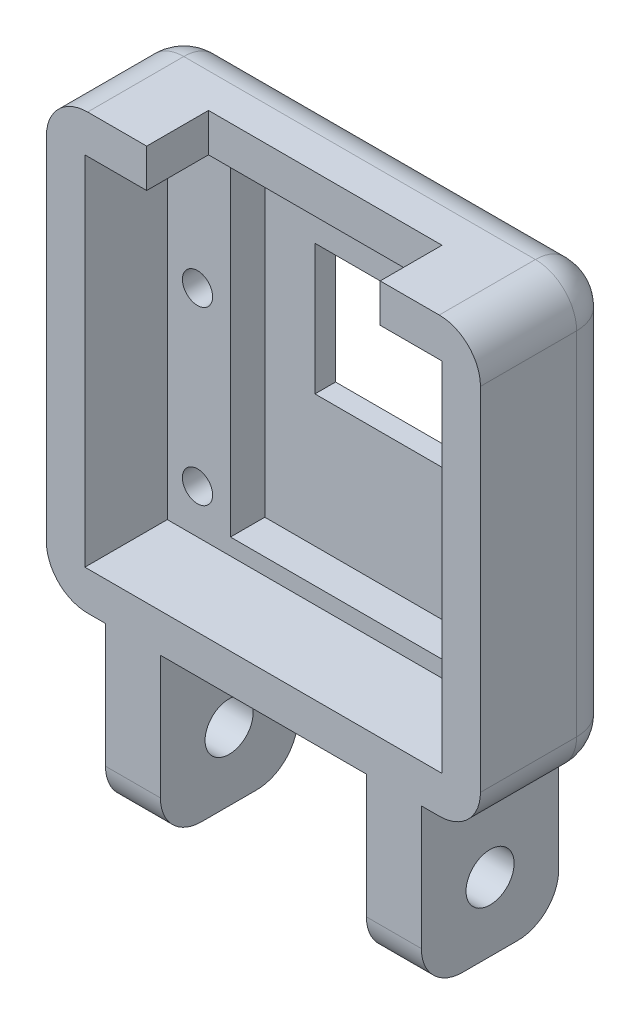
SolidWorks part; units mm, degrees
ref_plane "Front Plane" through (0, 0, 0) normal (0, 0, 1) x (1, 0, 0)
ref_plane "Top Plane" through (0, 0, 0) normal (0, 1, 0) x (1, 0, 0)
ref_plane "Right Plane" through (0, 0, 0) normal (1, 0, 0) x (0, 0, -1)
sketch "Sketch8" plane through (0, 0, 0) normal (0, 0, 1) x (1, 0, 0)
  line L1 (15.8, -15.8) -> (-15.8, -15.8)
  line L2 (15.8, -15.8) -> (15.8, 15.8)
  line L3 (15.8, 15.8) -> (-15.8, 15.8)
  line L4 (-15.8, -15.8) -> (-15.8, 15.8)
  line L5 (15.8, -15.8) -> (-15.8, 15.8) construction
  line L6 (15.8, 15.8) -> (-15.8, -15.8) construction
  line L7 (13, -13) -> (-13, -13)
  line L8 (13, -13) -> (13, 13)
  line L9 (13, 13) -> (-13, 13)
  line L10 (-13, -13) -> (-13, 13)
  line L11 (13, -13) -> (-13, 13) construction
  line L12 (13, 13) -> (-13, -13) construction
  line L13 (-10.8, 2.7) -> (10.8, 2.7)
  line L14 (-10.8, 2.7) -> (-10.8, -9.8)
  line L15 (-10.8, -9.8) -> (10.8, -9.8)
  line L16 (10.8, 2.7) -> (10.8, -9.8)
  line L17 (-4.75, -2.2) -> (4.75, -2.2)
  line L18 (-4.75, -2.2) -> (-4.75, 7.3)
  line L19 (-4.75, 7.3) -> (4.75, 7.3)
  line L20 (4.75, -2.2) -> (4.75, 7.3)
  line L21 (8.4, -11.8) -> (-8.4, -11.8)
  line L22 (8.4, -11.8) -> (8.4, 11.8)
  line L23 (8.4, 11.8) -> (-8.4, 11.8)
  line L24 (-8.4, -11.8) -> (-8.4, 11.8)
  line L25 (8.4, -11.8) -> (-8.4, 11.8) construction
  line L26 (-9, 15.8) -> (9, 15.8)
  line L27 (-9, 15.8) -> (-9, 13)
  line L28 (-9, 13) -> (9, 13)
  line L29 (9, 15.8) -> (9, 13)
  line L30 (8.4, 11.8) -> (-8.4, -11.8) construction
  point P0 (0, 0)
  point P5 (0, 0)
  point P13 (0, 7.3)
  point P27 (0, 0)
  dimension "D2" = 9.5
  dimension "D1" = 2.8
  dimension "D3" = 7.3
  dimension "D4" = 1.2
  dimension "D5" = 16.8
sketch "Sketch2" plane through (0, 0, 0) normal (0, 0, 1) x (1, 0, 0)
  line L1 (15.8, 15.8) -> (-15.8, 15.8)
  line L2 (15.8, 15.8) -> (15.8, -15.8)
  line L3 (15.8, -15.8) -> (-15.8, -15.8)
  line L4 (-15.8, 15.8) -> (-15.8, -15.8)
  line L5 (15.8, 15.8) -> (-15.8, -15.8) construction
  line L6 (15.8, -15.8) -> (-15.8, 15.8) construction
  point P0 (0, 0)
  dimension "D1" = 31.6
extrude "Boss-Extrude1" add sketch "Sketch2" along normal blind 10 separate body
sketch "Sketch13" plane through (0, -15.8, 0) normal (0, -1, 0) x (1, 0, 0)
  line L0 (-15.8, 10) -> (15.8, 10) construction
  line L1 (-11.5, 10) -> (-7.5, 10)
  line L2 (-11.5, 10) -> (-11.5, 0)
  line L3 (-11.5, 0) -> (-7.5, 0)
  line L4 (-7.5, 10) -> (-7.5, 0)
  line L5 (-15.8, 0) -> (15.8, 0) construction
  line L7 (7.5, 10) -> (11.5, 10)
  line L8 (7.5, 10) -> (7.5, 0)
  line L9 (7.5, 0) -> (11.5, 0)
  line L10 (11.5, 10) -> (11.5, 0)
  dimension "D1" = 15
  dimension "D2" = 7.5
  dimension "D3" = 4
extrude "Boss-Extrude2" add sketch "Sketch13" along normal blind 12
sketch "Sketch14" plane through (-11.5, 0, 0) normal (-1, 0, 0) x (0, 0, 1)
  line L0 (10, -27.8) -> (0, -27.8) construction
  circle A0 centre (5, -22.8) radius 1.75
  dimension "D1" = 5
  dimension "D2" = 3.5
extrude "Cut-Extrude5" cut sketch "Sketch14" against normal blind 30
sketch "Sketch9" plane through (0, 0, 10) normal (0, 0, 1) x (1, 0, 0)
  line L1 (-13, 13) -> (13, 13)
  line L2 (-13, 13) -> (-13, -13)
  line L3 (-13, -13) -> (13, -13)
  line L4 (13, 13) -> (13, -13)
extrude "Cut-Extrude1" cut sketch "Sketch9" against normal blind 6
sketch "Sketch10" plane through (0, 0, 4) normal (0, 0, 1) x (1, 0, 0)
  line L0 (13, 13) -> (-13, 13) construction
  line L1 (8.4, -11.8) -> (-8.4, -11.8)
  line L2 (8.4, -11.8) -> (8.4, 11.8)
  line L3 (8.4, 11.8) -> (-8.4, 11.8)
  line L4 (-8.4, -11.8) -> (-8.4, 11.8)
  line L5 (8.4, -11.8) -> (-8.4, 11.8) construction
  line L6 (8.4, 11.8) -> (-8.4, -11.8) construction
  point P0 (0, 0)
  dimension "D1" = 16.8
  dimension "D2" = 1.2
extrude "Cut-Extrude2" cut sketch "Sketch10" against normal blind 2.5
sketch "Sketch11" plane through (0, 0, 1.5) normal (0, 0, 1) x (1, 0, 0)
  line L1 (-4.75, 7.3) -> (4.75, 7.3)
  line L2 (-4.75, 7.3) -> (-4.75, -2.2)
  line L3 (-4.75, -2.2) -> (4.75, -2.2)
  line L4 (4.75, 7.3) -> (4.75, -2.2)
extrude "Cut-Extrude3" cut sketch "Sketch11" against normal blind 2.5
sketch "Sketch12" plane through (0, 0, 4) normal (0, 0, 1) x (1, 0, 0)
  circle A0 centre (-10.8, 2.7) radius 1.1
  circle A1 centre (10.8, 2.7) radius 1.1
  circle A2 centre (10.8, -9.8) radius 1.1
  circle A3 centre (-10.8, -9.8) radius 1.1
  dimension "D1" = 2.2
extrude "Cut-Extrude4" cut sketch "Sketch12" against normal blind 3
fillet "Fillet1" radius 3 14 edges at (0, 15.8, 0) (-15.8, 0, 0) (-13.65, -15.8, 0) (13.65, -15.8, 0) (15.8, 0, 0) (15.8, -15.8, 5) (-15.8, -15.8, 5) (-15.8, 15.8, 5) (15.8, 15.8, 5) (9.5, -27.8, 0) (9.5, -27.8, 10) (-9.5, -27.8, 10) (-9.5, -27.8, 0) (0, -15.8, 0)
sketch "Sketch15" plane through (0, 0, 10) normal (0, 0, 1) x (1, 0, 0)
  line L0 (12.8, 15.8) -> (-12.8, 15.8) construction
  line L1 (-8.5, 15.8) -> (8.5, 15.8)
  line L2 (-8.5, 15.8) -> (-8.5, 13)
  line L3 (-8.5, 13) -> (8.5, 13)
  line L4 (8.5, 15.8) -> (8.5, 13)
  line L5 (13, 13) -> (-13, 13) construction
  line L6 (-12.8, 15.8) -> (12.8, 15.8) construction
  point P8 (0, 15.8)
  dimension "D1" = 17
extrude "Cut-Extrude6" cut sketch "Sketch15" against normal blind 4.5
